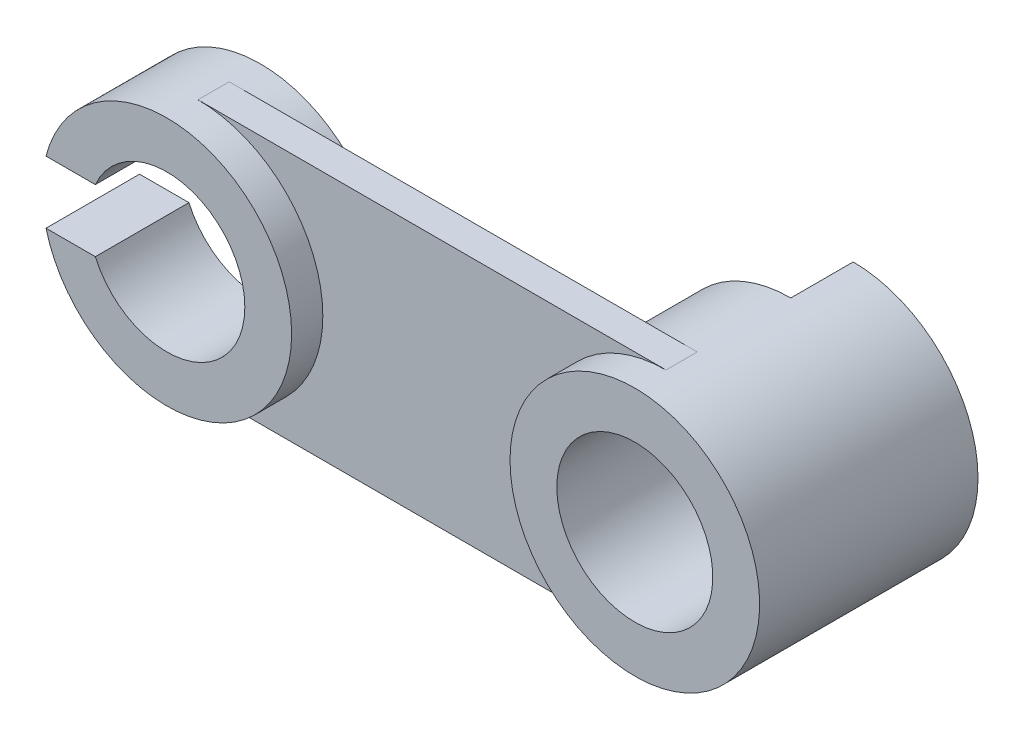
SolidWorks part; units mm, degrees
ref_plane "Front Plane" through (0, 0, 0) normal (0, 0, 1) x (1, 0, 0)
ref_plane "Top Plane" through (0, 0, 0) normal (0, 1, 0) x (1, 0, 0)
ref_plane "Right Plane" through (0, 0, 0) normal (1, 0, 0) x (0, 0, -1)
sketch "Sketch1" plane through (0, 0, 0) normal (0, 0, 1) x (1, 0, 0)
  line L1 (-37.5, -20) -> (37.5, -20)
  line L2 (-37.5, -20) -> (-37.5, 20)
  line L3 (-37.5, 20) -> (37.5, 20)
  line L4 (37.5, -20) -> (37.5, 20)
  line L5 (-37.5, -20) -> (37.5, 20) construction
  line L6 (-37.5, 20) -> (37.5, -20) construction
  point P0 (0, 0)
  dimension "D1" = 75
  dimension "D2" = 40
extrude "Boss-Extrude1" add sketch "Sketch1" along normal blind 5
sketch "Sketch4" plane through (0, 0, 5) normal (0, 0, 1) x (1, 0, 0)
  line L0 (-37.5, 20) -> (-37.5, -20) construction
  circle A0 centre (-37.5, 0) radius 20
extrude "Boss-Extrude2" add sketch "Sketch4" against normal blind 10 and the other way blind 5
sketch "Sketch6" plane through (0, 0, 10) normal (0, 0, 1) x (1, 0, 0)
  line L1 (-57.5, -5) -> (-57.5, 5)
  line L2 (-57.5, 5) -> (-48.9564, 5)
  line L5 (-57.5, -5) -> (-48.9564, -5)
  arc A0 (-48.9564, -5) -> (-48.9564, 5) centre (-37.5, 0) ccw
extrude "Cut-Extrude4" cut sketch "Sketch6" against normal blind 15
sketch "Sketch8" plane through (0, 0, 0) normal (0, 0, -1) x (-1, 0, 0)
  line L0 (-37.5, -20) -> (-37.5, 20) construction
  circle A0 centre (-37.5, 0) radius 20
extrude "Boss-Extrude3" add sketch "Sketch8" along normal blind 15 and the other way blind 10
sketch "Sketch9" plane through (0, 0, -15) normal (0, 0, -1) x (-1, 0, 0)
  circle A0 centre (-37.5, 0) radius 12.5
  dimension "D1" = 25
extrude "Cut-Extrude5" cut sketch "Sketch9" against normal blind 25
sketch "Sketch10" plane through (0, 0, -15) normal (0, 0, -1) x (-1, 0, 0)
  line L0 (-37.5, -20) -> (-37.5, -12.5)
  line L1 (-37.5, 12.5) -> (-37.5, 20)
  arc A0 (-37.5, 20) -> (-37.5, -20) centre (-37.5, 0) ccw
  arc A1 (-37.5, 12.5) -> (-37.5, -12.5) centre (-37.5, 0) ccw
extrude "Boss-Extrude4" add sketch "Sketch10" along normal blind 10
ref_plane "Plane2" through (0, 0, 0) normal (0, 1, 0) x (1, 0, 0)
sketch "Sketch11" plane through (0, 0, 0) normal (0, 1, 0) x (1, 0, 0)
  line L0 (17.5, 15) -> (-2.5, 0)
  line L1 (37.5, 0) -> (-37.5, 0) construction
  line L2 (17.5, 15) -> (17.5, 0)
  line L3 (17.5, 15) -> (17.5, 0) construction
  line L4 (17.5, 0) -> (-2.5, 0)
  dimension "D1" = 20
extrude "Boss-Extrude5" add sketch "Sketch11" along normal mid plane 5 separate body
